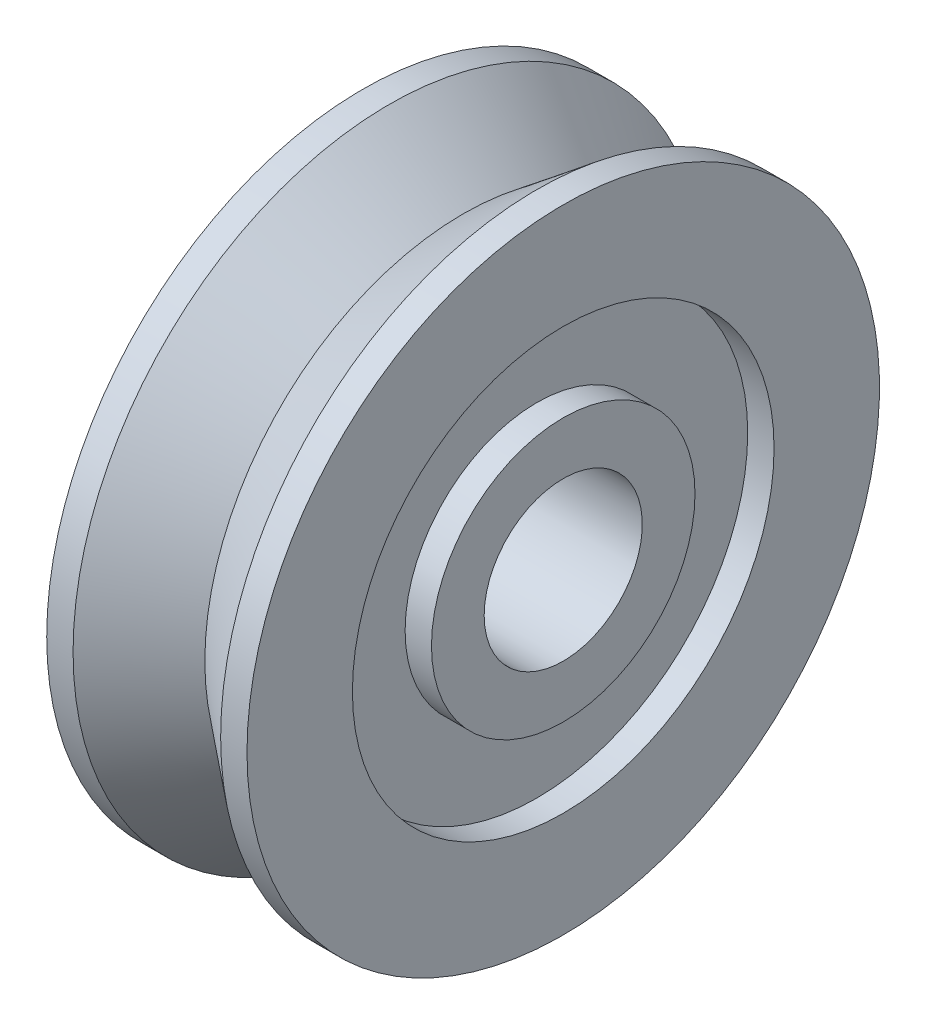
SolidWorks part; units mm, degrees
material "合金钢 (SS)"
ref_plane "前视基准面" through (0, 0, 0) normal (0, 0, 1) x (1, 0, 0)
ref_plane "上视基准面" through (0, 0, 0) normal (0, 1, 0) x (1, 0, 0)
ref_plane "右视基准面" through (0, 0, 0) normal (1, 0, 0) x (0, 0, -1)
sketch "草图1" plane through (0, 0, 0) normal (0, 0, 1) x (1, 0, 0)
  line L0 (-1.9, 1.5) -> (1.9, 1.5)
  line L1 (1.9, 1.5) -> (1.9, 2.5)
  line L2 (1.9, 2.5) -> (1.4, 2.5)
  line L3 (1.4, 2.5) -> (1.4, 4)
  line L4 (1.4, 4) -> (1.9, 4)
  line L5 (1.9, 4) -> (1.9, 6)
  line L6 (1.9, 6) -> (1.4, 6)
  line L7 (1.4, 6) -> (0, 4.9)
  line L8 (0, 4.9) -> (-1.4, 6)
  line L9 (-1.4, 6) -> (-1.9, 6)
  line L10 (-1.9, 6) -> (-1.9, 4)
  line L11 (-1.9, 4) -> (-1.4, 4)
  line L12 (-1.4, 4) -> (-1.4, 2.5)
  line L13 (-1.4, 2.5) -> (-1.9, 2.5)
  line L14 (-1.9, 2.5) -> (-1.9, 1.5)
  line L15 (0, 0) -> (0, 1.5) construction
  line L16 (0, 4.9) -> (0, 1.5) construction
  line L17 (0, 0) -> (1.9, 0) construction
  dimension "D1" = 1.1
  dimension "D2" = 0.5
  dimension "D3" = 1.5
  dimension "D4" = 1.4
  dimension "D5" = 6
  dimension "D6" = 2
  dimension "D7" = 1
revolve "旋转1" add sketch "草图1" angle 360 about L17
